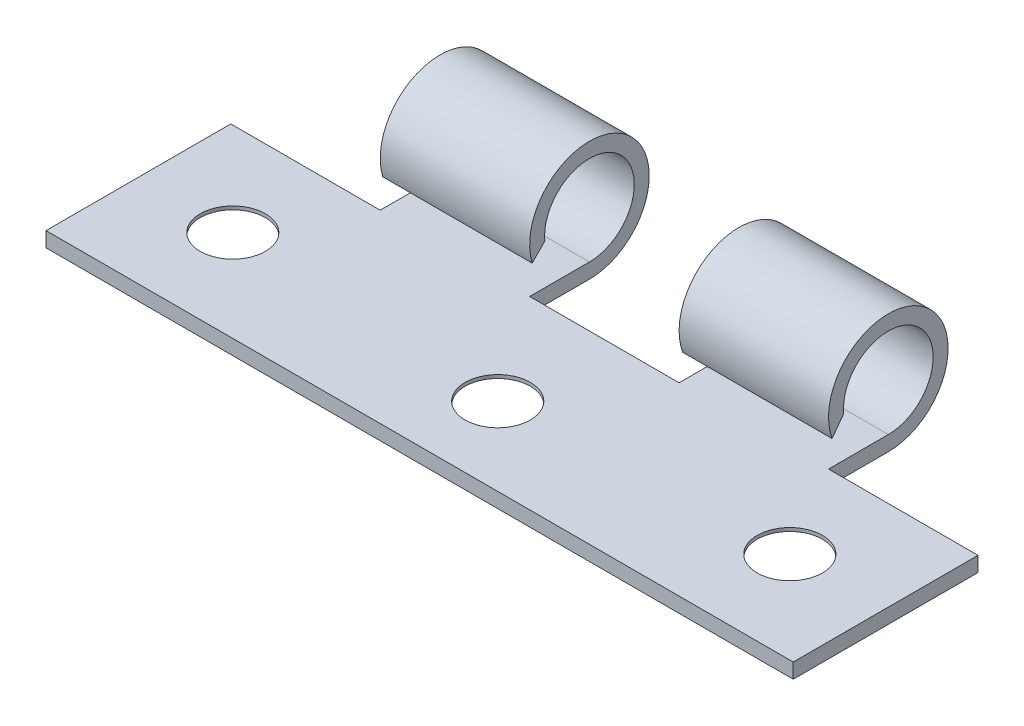
SolidWorks part; units mm, degrees
material "AISI 304"
ref_plane "Front Plane" through (0, 0, 0) normal (0, 0, 1) x (1, 0, 0)
ref_plane "Top Plane" through (0, 0, 0) normal (0, 1, 0) x (1, 0, 0)
ref_plane "Right Plane" through (0, 0, 0) normal (1, 0, 0) x (0, 0, -1)
ref_plane "Plane1" through (62.103, 0, 0) normal (1, 0, 0) x (0, 0, -1)
sketch "Sketch1" plane through (62.103, 0, 0) normal (1, 0, 0) x (0, 0, -1)
  line L0 (34.275, 2.9168) -> (35.1337, 4.0734)
  line L1 (38.4175, 1.1) -> (20.4175, 1.1)
  line L2 (20.4175, 1.1) -> (20.4175, 0)
  line L3 (20.4175, 0) -> (38.4175, 0)
  line L5 (34.0175, 4.4) -> (34.0175, 0) construction
  arc A0 (38.4175, 0) -> (34.275, 2.9168) centre (38.4175, 4.4) ccw
  arc A1 (35.1337, 4.0734) -> (38.4175, 1.1) centre (38.4175, 4.4) cw
  dimension "D1" = 4.4
  dimension "3.3" = 3.3
  dimension "D2" = 13.6
extrude "Boss-Extrude1" add sketch "Sketch1" against normal blind 11
sketch "Sketch2" plane through (51.103, 0, 0) normal (-1, 0, 0) x (0, 0, 1)
  line L0 (-20.4175, 0) -> (-34.0175, 0)
  line L1 (-34.0175, 0) -> (-34.0175, 1.1)
  line L2 (-34.0175, 1.1) -> (-20.4175, 1.1)
  line L3 (-20.4175, 1.1) -> (-20.4175, 0)
  line L4 (-20.4175, 1.1) -> (-20.4175, 0) construction
  line L6 (-34.0175, 4.4) -> (-34.0175, 0) construction
  line L7 (-38.4175, 1.1) -> (-20.4175, 1.1) construction
  arc A0 (-34.275, 2.9168) -> (-38.4175, 0) centre (-38.4175, 4.4) ccw construction
  dimension "D1" = 1.1
extrude "Boss-Extrude2" add sketch "Sketch2" along normal blind 11
sketch "Sketch3" plane through (40.103, 0, 0) normal (-1, 0, 0) x (0, 0, 1)
  line L0 (-38.4175, 1.1) -> (-20.4175, 1.1)
  line L1 (-20.4175, 1.1) -> (-20.4175, 0)
  line L2 (-20.4175, 0) -> (-38.4175, 0)
  line L3 (-34.0175, 0) -> (-20.4175, 0) construction
  line L4 (-20.4175, 0) -> (-20.4175, 1.1) construction
  line L6 (-35.1337, 4.0734) -> (-34.2036, 3.1339)
  line L7 (-34.0175, 4.4) -> (-34.0175, 0) construction
  line L8 (-34.275, 2.9168) -> (-35.1337, 4.0734) construction
  arc A0 (-38.4175, 0) -> (-34.2036, 3.1339) centre (-38.4175, 4.4) cw
  arc A1 (-35.1337, 4.0734) -> (-38.4175, 1.1) centre (-38.4175, 4.4) ccw
  dimension "D1" = 4.4
  dimension "D2" = 3.3
  dimension "D3" = 13.6
extrude "Boss-Extrude3" add sketch "Sketch3" along normal blind 11
sketch "Sketch4" plane through (29.103, 0, 0) normal (-1, 0, 0) x (0, 0, 1)
  line L0 (-34.0175, 1.1) -> (-20.4175, 1.1)
  line L1 (-20.4175, 1.1) -> (-20.4175, 0)
  line L2 (-20.4175, 0) -> (-34.0175, 0)
  line L3 (-34.0175, 0) -> (-34.0175, 1.1)
  dimension "D1" = 13.6
  dimension "D3" = 1.1
extrude "Boss-Extrude4" add sketch "Sketch4" along normal blind 11
sketch "Sketch5" plane through (62.103, 0, 0) normal (1, 0, 0) x (0, 0, -1)
  line L0 (34.0175, 1.1) -> (34.0175, 0)
  line L1 (34.0175, 0) -> (20.4175, 0)
  line L2 (20.4175, 0) -> (20.4175, 1.1)
  line L3 (20.4175, 1.1) -> (34.0175, 1.1)
  line L5 (34.0175, 4.4) -> (34.0175, 0) construction
  arc A1 (38.4175, 0) -> (34.275, 2.9168) centre (38.4175, 4.4) ccw construction
  dimension "D1" = 0
  dimension "D2" = 13.6
  dimension "D3" = 1.1
extrude "Boss-Extrude5" add sketch "Sketch5" along normal blind 11
hole_wizard "M4 间隙孔1" positions "Sketch7" profile "Sketch6" hole size "M4" standard "ANSI Metric" end condition through all
sketch "Sketch7" plane through (0, 1.1, 0) normal (0, 1, 0) x (1, 0, 0)
  line L2 (40.103, 34.0175) -> (51.103, 34.0175) construction
  line L3 (45.603, 34.0175) -> (45.603, 20.4175) construction
  line L4 (18.103, 20.4175) -> (73.103, 20.4175) construction
  point P0 (45.603, 26.1675)
  point P1 (25.103, 27.1675)
  point P2 (66.103, 27.1675)
  dimension "D1" = 5.75
  dimension "D2" = 20.5
  dimension "D3" = 20.5
  dimension "D4" = 6.75
sketch "Sketch6" plane through (45.603, 1.1, -26.1675) normal (1, 0, 0) x (0, 0, 1)
  line L0 (0, 0) -> (0, 1.1)
  line L1 (0, 1.1) -> (2.4, 1.1)
  line L2 (2.4, 1.1) -> (2.4, 0)
  line L5 (2.4, 0) -> (0, 0)
  line L11 (0, -6.35) -> (0, 107.95) construction
  dimension "Thru Hole Dia." = 4.8
  dimension "Thru Hole Depth" = 1.1
chamfer "Chamfer1" distance 0.85 angle 60 3 edges at (66.103, 0, -24.7675) (45.603, 0, -23.7675) (25.103, 0, -24.7675)
